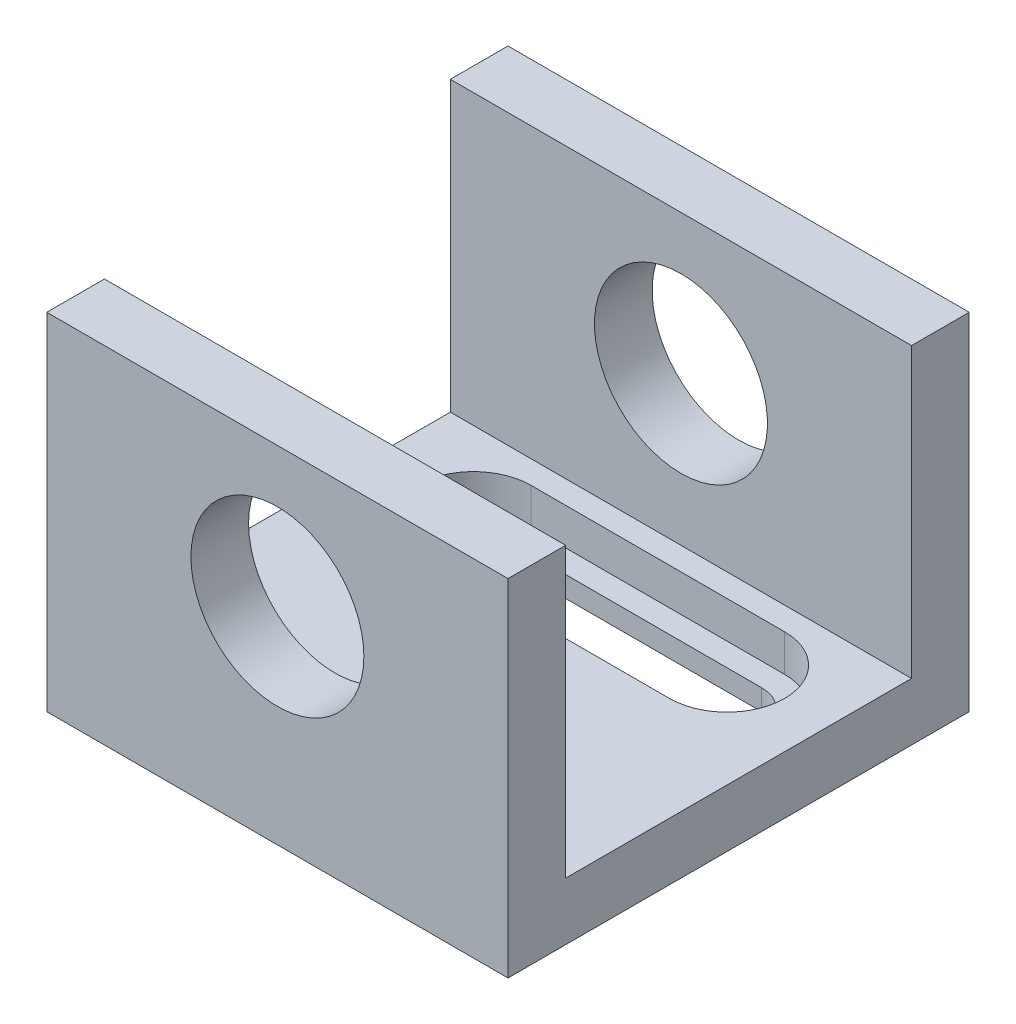
SolidWorks part; units mm, degrees
ref_plane "Front Plane" through (0, 0, 0) normal (0, 0, 1) x (1, 0, 0)
ref_plane "Top Plane" through (0, 0, 0) normal (0, 1, 0) x (1, 0, 0)
ref_plane "Right Plane" through (0, 0, 0) normal (1, 0, 0) x (0, 0, -1)
sketch "Sketch1" plane through (-35.1459, 0, 0) normal (1, 0, 0) x (0, 0, -1)
  line L1 (0, 0) -> (-19.05, 0)
  line L3 (0, 3.175) -> (-19.05, 3.175)
  line L5 (3.175, 19.05) -> (0, 19.05)
  line L6 (3.175, 19.05) -> (3.175, 0)
  line L7 (3.175, 0) -> (0, 0)
  line L8 (0, 19.05) -> (0, 3.175)
  line L13 (-19.05, 0) -> (-22.225, 0)
  line L14 (-19.05, 3.175) -> (-19.05, 19.05)
  line L15 (-19.05, 19.05) -> (-22.225, 19.05)
  line L16 (-22.225, 0) -> (-22.225, 19.05)
  dimension "D2" = 3.175
  dimension "D3" = 3.175
  dimension "D4" = 19.05
  dimension "D5" = 19.05
extrude "Boss-Extrude2" add sketch "Sketch1" along normal blind 25.4
sketch "Sketch3" plane through (0, 0, -3.175) normal (0, 0, -1) x (-1, 0, 0)
  line L0 (9.7459, 0) -> (35.1459, 0) construction
  line L2 (35.1459, 0) -> (35.1459, 19.05) construction
  circle A0 centre (22.4459, 11.3665) radius 4.7625
  point P2 (0, 0)
  dimension "D1" = 11.3665
  dimension "D2" = 12.7
extrude "Cut-Extrude1" cut sketch "Sketch3" against normal blind 36.576
sketch "Sketch4" plane through (0, 3.175, 0) normal (0, 1, 0) x (1, 0, 0)
  line L1 (-29.4309, -1.27) -> (-15.4609, -1.27)
  line L3 (-29.4309, -2.54) -> (-15.4609, -2.54)
  line L5 (-29.4309, -6.35) -> (-15.4609, -6.35)
  line L7 (-29.4309, -7.62) -> (-15.4609, -7.62)
  line L9 (-9.7459, -19.05) -> (-35.1459, -19.05) construction
  line L10 (-29.4309, -1.27) -> (-15.4609, -1.27)
  line L11 (-15.4609, -7.62) -> (-29.4309, -7.62)
  arc A0 (-29.4309, -2.54) -> (-29.4309, -6.35) centre (-29.4309, -4.445) ccw
  arc A1 (-29.4309, -1.27) -> (-29.4309, -7.62) centre (-29.4309, -4.445) ccw
  arc A2 (-15.4609, -2.54) -> (-15.4609, -6.35) centre (-15.4609, -4.445) cw
  arc A3 (-15.4609, -1.27) -> (-15.4609, -7.62) centre (-15.4609, -4.445) cw
  arc A4 (-29.4309, -1.27) -> (-29.4309, -7.62) centre (-29.4309, -4.445) ccw
  arc A5 (-15.4609, -1.27) -> (-15.4609, -7.62) centre (-15.4609, -4.445) cw
  dimension "D1" = 1.27
  dimension "D4" = 1.27
  dimension "D5" = 3.81
  dimension "D6" = 12.7
extrude "Cut-Extrude2" cut sketch "Sketch4" against normal blind 66.04 contours L3 A2 L5 A0
sketch "Sketch7" plane through (0, 3.175, 0) normal (0, 1, 0) x (1, 0, 0)
  line L1 (-29.4309, -2.54) -> (-15.4609, -2.54)
  line L3 (-29.4309, -1.27) -> (-15.4609, -1.27)
  line L5 (-29.4309, -6.35) -> (-15.4609, -6.35)
  line L7 (-29.4309, -7.62) -> (-15.4609, -7.62)
  arc A0 (-29.4309, -1.27) -> (-29.4309, -7.62) centre (-29.4309, -4.445) ccw
  arc A1 (-15.4609, -1.27) -> (-15.4609, -7.62) centre (-15.4609, -4.445) cw
  dimension "D1" = 1.27
  dimension "D2" = 13.97
  dimension "D3" = 1.27
  dimension "D4" = 13.97
extrude "Cut-Extrude3" cut sketch "Sketch7" against normal blind 2.032 contours L3 A1 L7 A0
